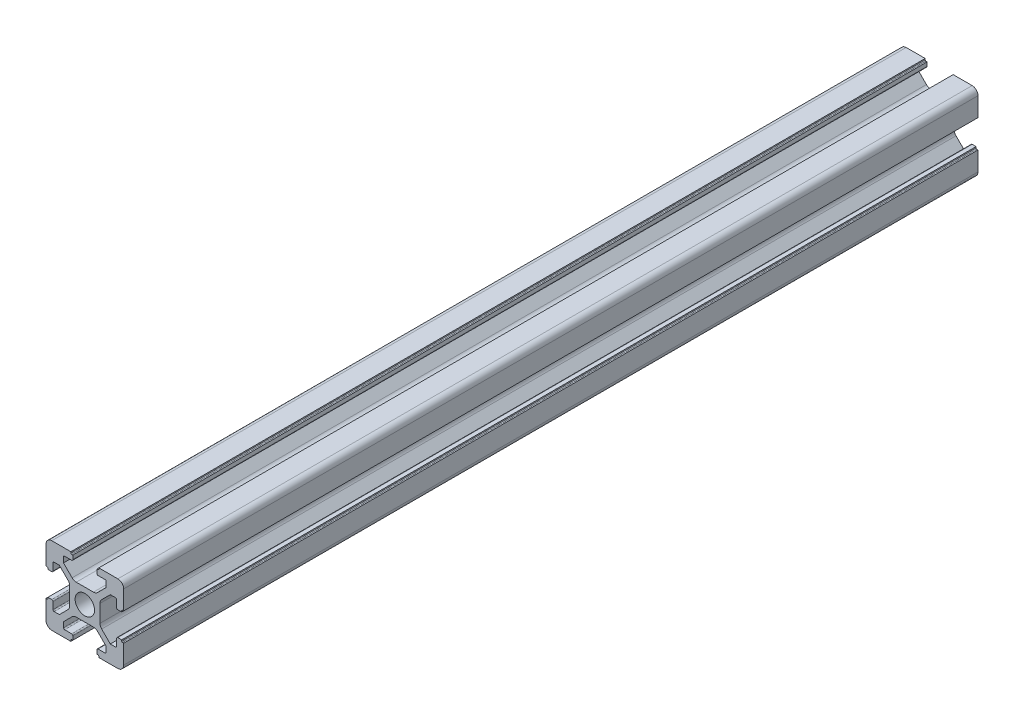
SolidWorks part; units mm, degrees
ref_plane "前视基准面" through (0, 0, 0) normal (0, 0, 1) x (1, 0, 0)
ref_plane "上视基准面" through (0, 0, 0) normal (0, 1, 0) x (1, 0, 0)
ref_plane "右视基准面" through (0, 0, 0) normal (1, 0, 0) x (0, 0, -1)
sketch "草图1" plane through (0, 0, 0) normal (0, 0, 1) x (1, 0, 0)
  line L0 (4.216, 3.2442) -> (6.4367, 5.4649)
  line L1 (6.4367, 5.4649) -> (7.7767, 5.4649)
  line L2 (8.0767, 5.1649) -> (8.0767, 3.3649)
  line L3 (8.3767, 3.0649) -> (9.3767, 3.0649)
  line L4 (9.3767, 3.0649) -> (9.3767, 3.3649)
  line L5 (9.5767, 3.5649) -> (9.8767, 3.5649)
  line L6 (9.8767, 3.5649) -> (9.8767, 8.4649)
  line L7 (8.3767, 9.9649) -> (3.4767, 9.9649)
  line L8 (3.4767, 9.9649) -> (3.4767, 9.6649)
  line L9 (3.2767, 9.4649) -> (2.9767, 9.4649)
  line L10 (2.9767, 9.4649) -> (2.9767, 8.4649)
  line L11 (3.2767, 8.1649) -> (5.0767, 8.1649)
  line L12 (5.3767, 7.8649) -> (5.3767, 6.5249)
  line L13 (5.3767, 6.5249) -> (3.156, 4.3042)
  line L14 (2.0953, 3.8649) -> (-2.342, 3.8649)
  line L15 (-3.4027, 4.3042) -> (-5.6233, 6.5249)
  line L16 (-5.6233, 6.5249) -> (-5.6233, 7.8649)
  line L17 (-5.3233, 8.1649) -> (-3.5233, 8.1649)
  line L18 (-3.2233, 8.4649) -> (-3.2233, 9.4649)
  line L19 (-3.2233, 9.4649) -> (-3.5233, 9.4649)
  line L20 (-3.7233, 9.6649) -> (-3.7233, 9.9649)
  line L21 (-3.7233, 9.9649) -> (-8.6233, 9.9649)
  line L22 (-10.1233, 8.4649) -> (-10.1233, 3.5649)
  line L23 (-10.1233, 3.5649) -> (-9.8233, 3.5649)
  line L24 (-9.6233, 3.3649) -> (-9.6233, 3.0649)
  line L25 (-9.6233, 3.0649) -> (-8.6233, 3.0649)
  line L26 (-8.3233, 3.3649) -> (-8.3233, 5.1649)
  line L27 (-8.0233, 5.4649) -> (-6.6833, 5.4649)
  line L28 (-6.6833, 5.4649) -> (-4.4627, 3.2442)
  line L29 (-4.0233, 2.1836) -> (-4.0233, -2.2538)
  line L30 (-4.4627, -3.3144) -> (-6.6833, -5.5351)
  line L31 (-6.6833, -5.5351) -> (-8.0233, -5.5351)
  line L32 (-8.3233, -5.2351) -> (-8.3233, -3.4351)
  line L33 (-8.6233, -3.1351) -> (-9.6233, -3.1351)
  line L34 (-9.6233, -3.1351) -> (-9.6233, -3.4351)
  line L35 (-9.8233, -3.6351) -> (-10.1233, -3.6351)
  line L36 (-10.1233, -3.6351) -> (-10.1233, -8.5351)
  line L37 (-8.6233, -10.0351) -> (-3.7233, -10.0351)
  line L38 (-3.7233, -10.0351) -> (-3.7233, -9.7351)
  line L39 (-3.5233, -9.5351) -> (-3.2233, -9.5351)
  line L40 (-3.2233, -9.5351) -> (-3.2233, -8.5351)
  line L41 (-3.5233, -8.2351) -> (-5.3233, -8.2351)
  line L42 (-5.6233, -7.9351) -> (-5.6233, -6.5951)
  line L43 (-5.6233, -6.5951) -> (-3.4027, -4.3744)
  line L44 (-2.342, -3.9351) -> (2.0953, -3.9351)
  line L45 (3.156, -4.3744) -> (5.3767, -6.5951)
  line L46 (5.3767, -6.5951) -> (5.3767, -7.9351)
  line L47 (5.0767, -8.2351) -> (3.2767, -8.2351)
  line L48 (2.9767, -8.5351) -> (2.9767, -9.5351)
  line L49 (2.9767, -9.5351) -> (3.2767, -9.5351)
  line L50 (3.4767, -9.7351) -> (3.4767, -10.0351)
  line L51 (3.4767, -10.0351) -> (8.3767, -10.0351)
  line L52 (9.8767, -8.5351) -> (9.8767, -3.6351)
  line L53 (9.8767, -3.6351) -> (9.5767, -3.6351)
  line L54 (9.3767, -3.4351) -> (9.3767, -3.1351)
  line L55 (9.3767, -3.1351) -> (8.3767, -3.1351)
  line L56 (8.0767, -3.4351) -> (8.0767, -5.2351)
  line L57 (7.7767, -5.5351) -> (6.4367, -5.5351)
  line L58 (6.4367, -5.5351) -> (4.216, -3.3144)
  line L59 (3.7767, -2.2538) -> (3.7767, 2.1836)
  circle A0 centre (-0.1233, -0.0351) radius 2.5
  arc A1 (8.0767, 5.1649) -> (7.7767, 5.4649) centre (7.7767, 5.1649) ccw
  arc A2 (8.0767, 3.3649) -> (8.3767, 3.0649) centre (8.3767, 3.3649) ccw
  arc A3 (9.5767, 3.5649) -> (9.3767, 3.3649) centre (9.5767, 3.3649) ccw
  arc A4 (9.8767, 8.4649) -> (8.3767, 9.9649) centre (8.3767, 8.4649) ccw
  arc A5 (3.2767, 9.4649) -> (3.4767, 9.6649) centre (3.2767, 9.6649) ccw
  arc A6 (2.9767, 8.4649) -> (3.2767, 8.1649) centre (3.2767, 8.4649) ccw
  arc A7 (5.3767, 7.8649) -> (5.0767, 8.1649) centre (5.0767, 7.8649) ccw
  arc A8 (2.0953, 3.8649) -> (3.156, 4.3042) centre (2.0953, 5.3649) ccw
  arc A9 (-3.4027, 4.3042) -> (-2.342, 3.8649) centre (-2.342, 5.3649) ccw
  arc A10 (-5.3233, 8.1649) -> (-5.6233, 7.8649) centre (-5.3233, 7.8649) ccw
  arc A11 (-3.5233, 8.1649) -> (-3.2233, 8.4649) centre (-3.5233, 8.4649) ccw
  arc A12 (-3.7233, 9.6649) -> (-3.5233, 9.4649) centre (-3.5233, 9.6649) ccw
  arc A13 (-8.6233, 9.9649) -> (-10.1233, 8.4649) centre (-8.6233, 8.4649) ccw
  arc A14 (-9.6233, 3.3649) -> (-9.8233, 3.5649) centre (-9.8233, 3.3649) ccw
  arc A15 (-8.6233, 3.0649) -> (-8.3233, 3.3649) centre (-8.6233, 3.3649) ccw
  arc A16 (-8.0233, 5.4649) -> (-8.3233, 5.1649) centre (-8.0233, 5.1649) ccw
  arc A17 (-4.0233, 2.1836) -> (-4.4627, 3.2442) centre (-5.5233, 2.1836) ccw
  arc A18 (-4.4627, -3.3144) -> (-4.0233, -2.2538) centre (-5.5233, -2.2538) ccw
  arc A19 (-8.3233, -5.2351) -> (-8.0233, -5.5351) centre (-8.0233, -5.2351) ccw
  arc A20 (-8.3233, -3.4351) -> (-8.6233, -3.1351) centre (-8.6233, -3.4351) ccw
  arc A21 (-9.8233, -3.6351) -> (-9.6233, -3.4351) centre (-9.8233, -3.4351) ccw
  arc A22 (-10.1233, -8.5351) -> (-8.6233, -10.0351) centre (-8.6233, -8.5351) ccw
  arc A23 (-3.5233, -9.5351) -> (-3.7233, -9.7351) centre (-3.5233, -9.7351) ccw
  arc A24 (-3.2233, -8.5351) -> (-3.5233, -8.2351) centre (-3.5233, -8.5351) ccw
  arc A25 (-5.6233, -7.9351) -> (-5.3233, -8.2351) centre (-5.3233, -7.9351) ccw
  arc A26 (-2.342, -3.9351) -> (-3.4027, -4.3744) centre (-2.342, -5.4351) ccw
  arc A27 (3.156, -4.3744) -> (2.0953, -3.9351) centre (2.0953, -5.4351) ccw
  arc A28 (5.0767, -8.2351) -> (5.3767, -7.9351) centre (5.0767, -7.9351) ccw
  arc A29 (3.2767, -8.2351) -> (2.9767, -8.5351) centre (3.2767, -8.5351) ccw
  arc A30 (3.4767, -9.7351) -> (3.2767, -9.5351) centre (3.2767, -9.7351) ccw
  arc A31 (8.3767, -10.0351) -> (9.8767, -8.5351) centre (8.3767, -8.5351) ccw
  arc A32 (9.3767, -3.4351) -> (9.5767, -3.6351) centre (9.5767, -3.4351) ccw
  arc A33 (8.3767, -3.1351) -> (8.0767, -3.4351) centre (8.3767, -3.4351) ccw
  arc A34 (7.7767, -5.5351) -> (8.0767, -5.2351) centre (7.7767, -5.2351) ccw
  arc A35 (3.7767, -2.2538) -> (4.216, -3.3144) centre (5.2767, -2.2538) ccw
  arc A36 (4.216, 3.2442) -> (3.7767, 2.1836) centre (5.2767, 2.1836) ccw
extrude "凸台-拉伸1" add sketch "草图1" along normal blind 220
